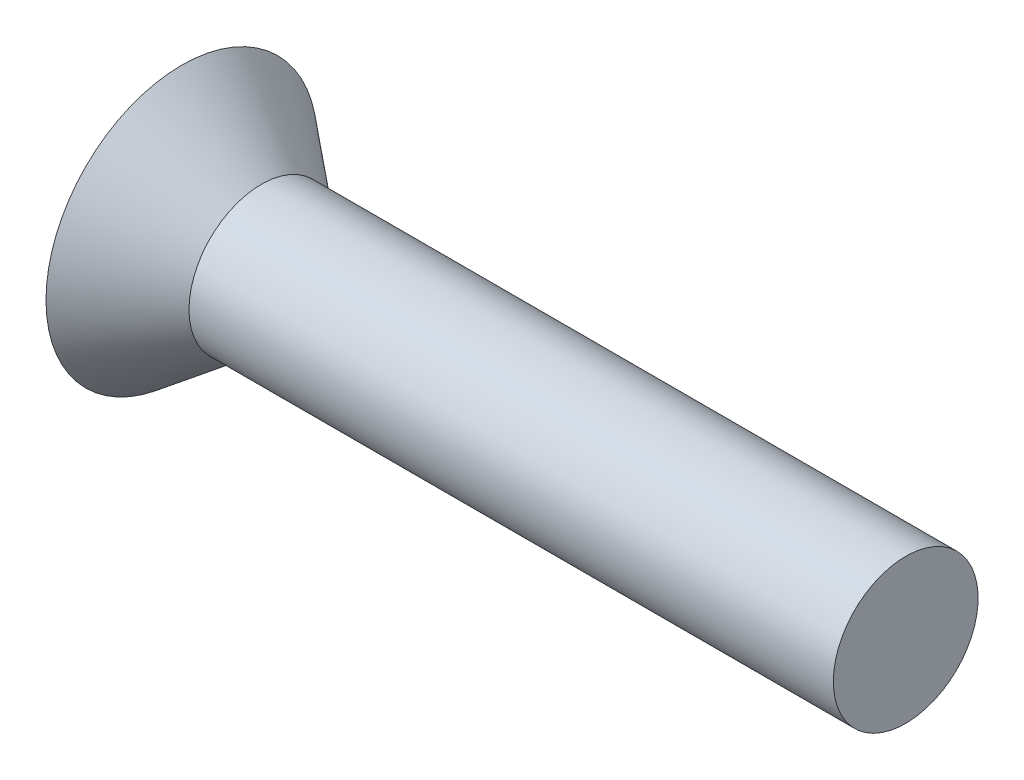
SolidWorks part; units mm, degrees
ref_plane "Спереди" through (0, 0, 0) normal (0, 0, 1) x (1, 0, 0)
ref_plane "Сверху" through (0, 0, 0) normal (0, 1, 0) x (1, 0, 0)
ref_plane "Справа" through (0, 0, 0) normal (1, 0, 0) x (0, 0, -1)
sketch "Sketch1" plane through (0, 0, 0) normal (0, 0, 1) x (1, 0, 0)
  line L0 (0, 0) -> (0, 3.75)
  line L1 (0, 3.75) -> (2.2, 2)
  line L2 (2.2, 2) -> (20, 2)
  line L3 (20, 2) -> (20, 0)
  line L4 (0, 0) -> (2.2, 0) construction
  line L5 (2.2, 0) -> (2.2, 2) construction
  line L6 (2.2, 2) -> (2.1733, 2.0376) construction
  line L7 (0, 0) -> (20, 0)
  dimension "D1" = 20
  dimension "D2" = 3.75
  dimension "D3" = 2
  dimension "D4" = 2.2
revolve "Revolve1" add sketch "Sketch1" angle 360 about L7
